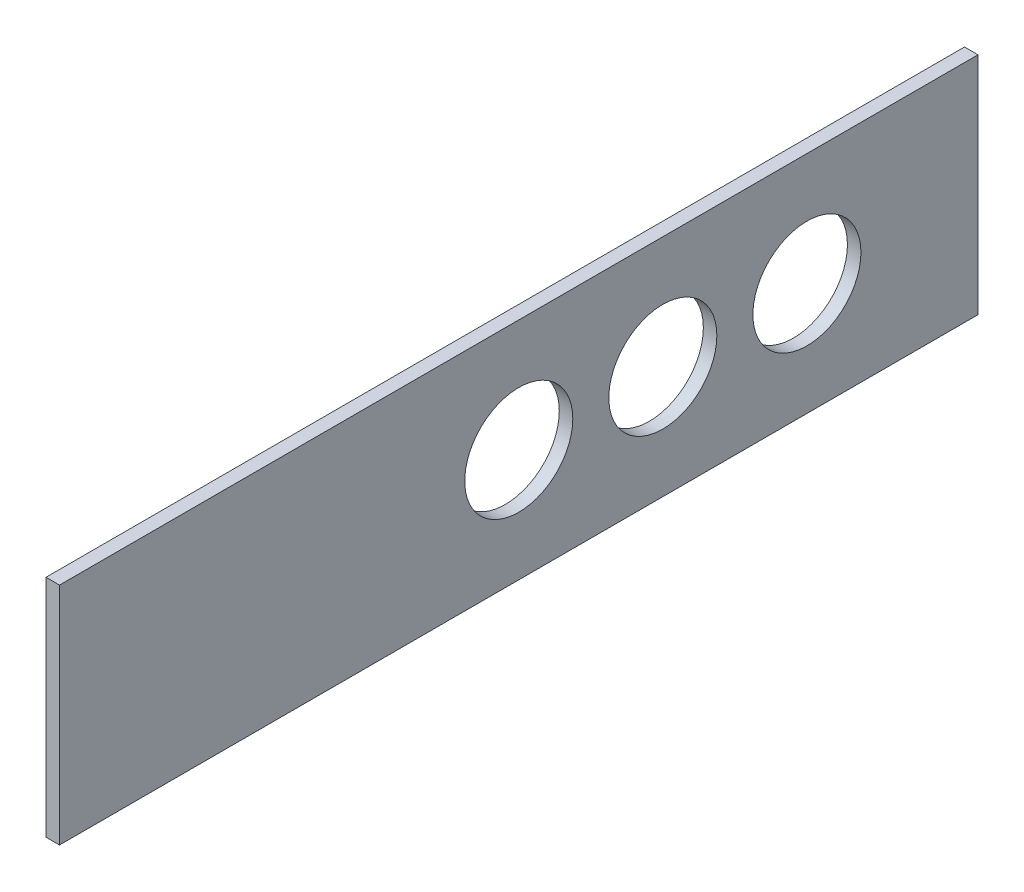
SolidWorks part; units mm, degrees
ref_plane "Front Plane" through (0, 0, 0) normal (0, 0, 1) x (1, 0, 0)
ref_plane "Top Plane" through (0, 0, 0) normal (0, 1, 0) x (1, 0, 0)
ref_plane "Right Plane" through (0, 0, 0) normal (1, 0, 0) x (0, 0, -1)
sketch "Sketch1" plane through (0, 0, 6.9966) normal (1, 0, 0) x (0, 0, -1)
  line L0 (97.3178, -12.1515) -> (97.3178, 12.8485)
  line L1 (-68.6822, 37.8485) -> (135.3178, 37.8485)
  line L2 (-68.6822, 37.8485) -> (-68.6822, -12.1515)
  line L3 (-68.6822, -12.1515) -> (135.3178, -12.1515)
  line L4 (135.3178, 37.8485) -> (135.3178, -12.1515)
  line L5 (97.3178, 12.8485) -> (135.3178, 12.8485)
  line L6 (97.3178, 12.8485) -> (65.3178, 12.8485)
  line L7 (65.3178, 12.8485) -> (33.3178, 12.8485)
  line L8 (33.3178, 12.8485) -> (1.3178, 12.8485)
  line L9 (1.3178, 12.8485) -> (-30.6822, 12.8485)
  line L10 (-68.6822, 12.8485) -> (-30.6822, 12.8485)
  circle A0 centre (97.3178, 12.8485) radius 12
  circle A3 centre (33.3178, 12.8485) radius 12
  circle A4 centre (65.3178, 12.8485) radius 12
  dimension "D3" = 25
  dimension "D5" = 38
  dimension "D1" = 204
  dimension "D2" = 50
  dimension "D4" = 38
  dimension "D6" = 32
  dimension "D7" = 32
  dimension "D8" = 32
  dimension "D10" = 32
extrude "Boss-Extrude1" add sketch "Sketch1" along normal blind 3
sketch "Sketch2" plane through (3, 0, 6.9966) normal (1, 0, 0) x (0, 0, -1)
sketch "Sketch5" plane through (3, 0, 0) normal (1, 0, 0) x (0, 0, -1)
